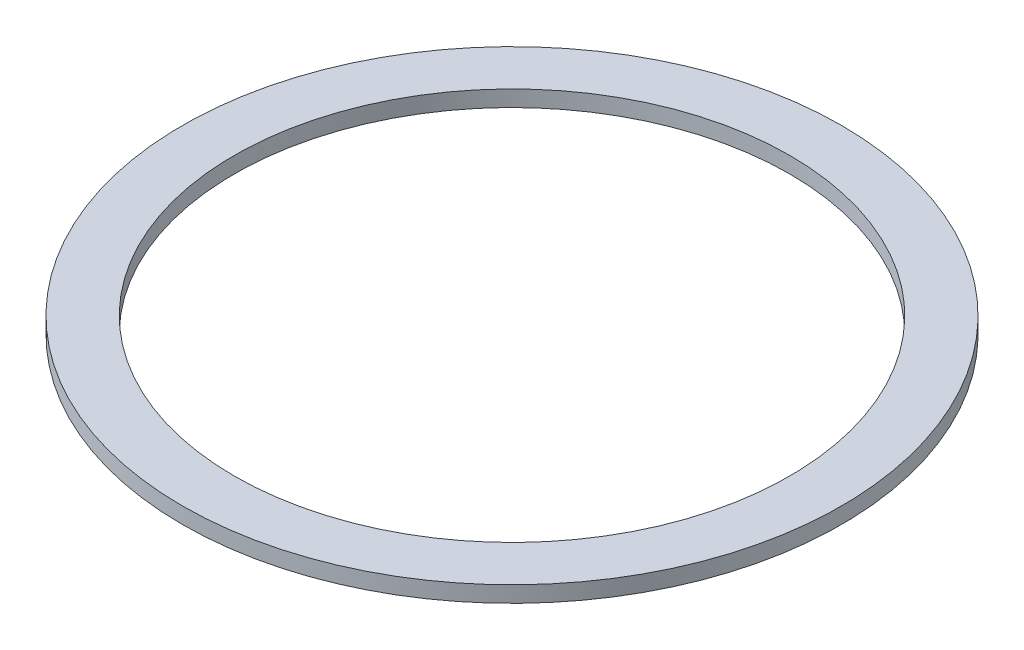
SolidWorks part; units mm, degrees
ref_plane "Front Plane" through (0, 0, 0) normal (0, 0, 1) x (1, 0, 0)
ref_plane "Top Plane" through (0, 0, 0) normal (0, 1, 0) x (1, 0, 0)
ref_plane "Right Plane" through (0, 0, 0) normal (1, 0, 0) x (0, 0, -1)
sketch "Sketch1" plane through (0, 0, 0) normal (0, 1, 0) x (1, 0, 0)
  circle A0 centre (0, 0) radius 32.75
  circle A1 centre (0, 0) radius 27.6
  dimension "D1" = 65.5
  dimension "D2" = 55.2
extrude "Boss-Extrude1" add sketch "Sketch1" along normal blind 1.6
